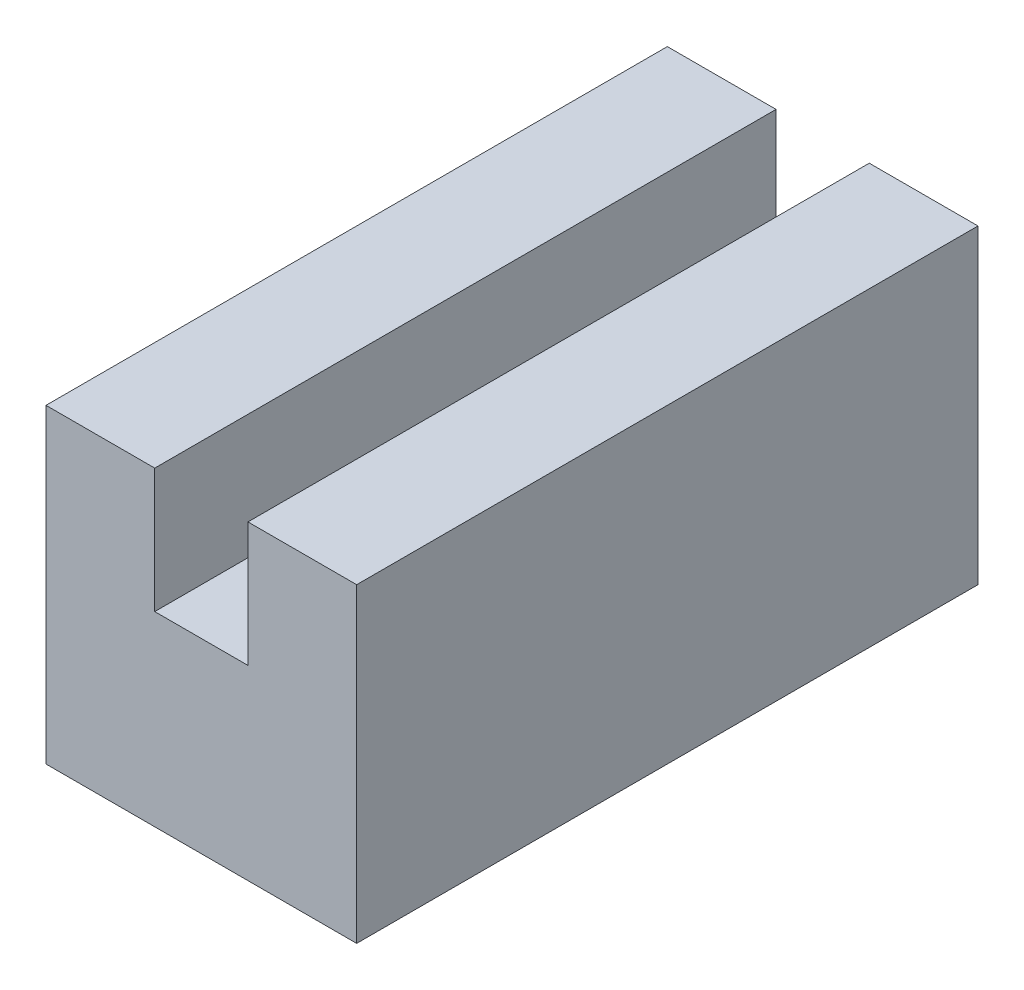
SolidWorks part; units mm, degrees
ref_plane "Front Plane" through (0, 0, 0) normal (0, 0, 1) x (1, 0, 0)
ref_plane "Top Plane" through (0, 0, 0) normal (0, 1, 0) x (1, 0, 0)
ref_plane "Right Plane" through (0, 0, 0) normal (1, 0, 0) x (0, 0, -1)
sketch "Sketch1" plane through (0, 0, 0) normal (0, 0, 1) x (1, 0, 0)
  line L1 (0, 0) -> (5, 0)
  line L2 (0, 0) -> (0, 5)
  line L3 (0, 5) -> (5, 5)
  line L4 (5, 0) -> (5, 5)
  dimension "D1" = 5
  dimension "D2" = 5
extrude "Boss-Extrude1" add sketch "Sketch1" along normal blind 10
sketch "Sketch2" plane through (0, 5, 0) normal (0, 1, 0) x (1, 0, 0)
  line L0 (5, 0) -> (0, 0) construction
  line L1 (1.75, 0) -> (3.25, 0)
  line L2 (1.75, 0) -> (1.75, -10)
  line L3 (1.75, -10) -> (3.25, -10)
  line L4 (3.25, 0) -> (3.25, -10)
  line L5 (5, -10) -> (0, -10) construction
  line L6 (0, -10) -> (0, 0) construction
  dimension "D1" = 1.5
  dimension "D2" = 1.75
extrude "Cut-Extrude1" cut sketch "Sketch2" against normal blind 2
